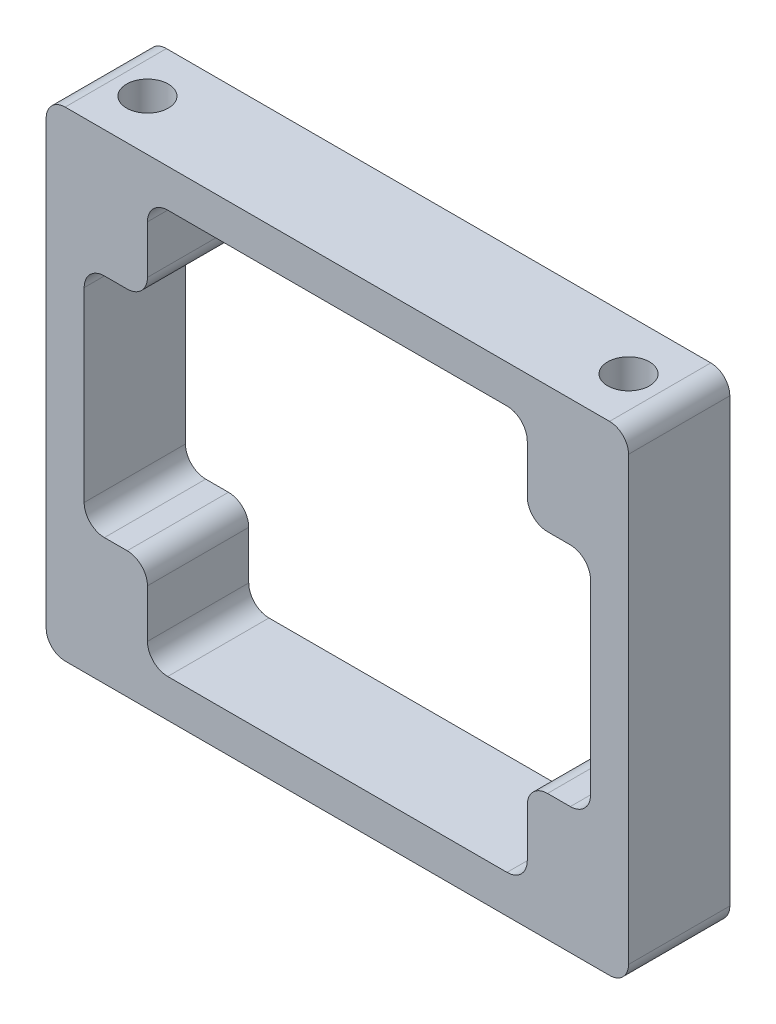
SolidWorks part; units mm, degrees
material "6061 合金"
ref_plane "前视基准面" through (0, 0, 0) normal (0, 0, 1) x (1, 0, 0)
ref_plane "上视基准面" through (0, 0, 0) normal (0, 1, 0) x (1, 0, 0)
ref_plane "右视基准面" through (0, 0, 0) normal (1, 0, 0) x (0, 0, -1)
other "Configuration Table"
sketch "草图1" plane through (0, 0, 0) normal (0, 0, 1) x (1, 0, 0)
  line L1 (-23, -18.95) -> (23, -18.95)
  line L2 (-23, -18.95) -> (-23, 18.95)
  line L3 (-23, 18.95) -> (23, 18.95)
  line L4 (23, -18.95) -> (23, 18.95)
  line L5 (-23, -18.95) -> (23, 18.95) construction
  line L6 (-23, 18.95) -> (23, -18.95) construction
  point P0 (0, 0)
  dimension "D1" = 46
  dimension "D2" = 37.9
extrude "凸台-拉伸1" add sketch "草图1" along normal mid plane 8
sketch "草图2" plane through (0, 18.95, 0) normal (0, 1, 0) x (1, 0, 0)
  line L0 (-19, 0) -> (19, 0) construction
  line L1 (23, -4) -> (23, 4) construction
  point P4 (0, 0)
  dimension "D1" = 4
hole_wizard "M4 螺纹孔1" positions "草图3" profile "草图4" tap size "M4" standard "GB"
sketch "草图3" plane through (0, 18.95, 0) normal (0, 1, 0) x (1, 0, 0)
  point P0 (-19, 0)
  point P3 (19, 0)
sketch "草图4" plane through (-19, 18.95, 0) normal (1, 0, 0) x (0, 0, 1)
  line L0 (0, 0) -> (0, 9.5914)
  line L1 (0, 9.5914) -> (1.65, 8.6)
  line L2 (1.65, 8.6) -> (1.65, 0)
  line L5 (1.65, 0) -> (0, 0)
  line L10 (0, 9.5914) -> (-1.65, 8.6) construction
  line L11 (0, -6.35) -> (0, 107.95) construction
  dimension "螺纹孔钻头直径" = 3.3
  dimension "螺纹孔钻头深度" = 8.6
  dimension "导头角度" = 118
cosmetic thread "孔螺蚊线1" parameters "D1"=6.5, "D2"=4
cosmetic thread "孔螺蚊线2" parameters "D1"=6.5, "D2"=4
mirror "镜向1" about plane through (0, 0, 0) normal (0, 1, 0) of "M4 螺纹孔1"
sketch "草图5" plane through (0, 0, 4) normal (0, 0, 1) x (1, 0, 0)
  line L0 (23, 18.95) -> (-23, 18.95) construction
  line L1 (-15, -15.95) -> (15, -15.95)
  line L2 (-15, -15.95) -> (-15, 15.95)
  line L3 (-15, 15.95) -> (15, 15.95)
  line L4 (15, -15.95) -> (15, 15.95)
  line L5 (-15, -15.95) -> (15, 15.95) construction
  line L6 (-15, 15.95) -> (15, -15.95) construction
  line L7 (23, -18.95) -> (23, 18.95) construction
  point P0 (0, 0)
  dimension "D1" = 3
  dimension "D2" = 8
extrude "切除-拉伸1" cut sketch "草图5" against normal mid plane 38
sketch "草图6" plane through (0, 0, 4) normal (0, 0, 1) x (1, 0, 0)
  line L0 (23, -18.95) -> (23, 18.95) construction
  line L1 (-20, -8.95) -> (20, -8.95)
  line L2 (-20, -8.95) -> (-20, 8.95)
  line L3 (-20, 8.95) -> (20, 8.95)
  line L4 (20, -8.95) -> (20, 8.95)
  line L5 (-20, -8.95) -> (20, 8.95) construction
  line L6 (-20, 8.95) -> (20, -8.95) construction
  line L7 (23, 18.95) -> (-23, 18.95) construction
  point P0 (0, 0)
  dimension "D1" = 3
  dimension "D2" = 10
extrude "切除-拉伸2" cut sketch "草图6" against normal mid plane 68
fillet "圆角1" radius 1.6 12 edges at (-15, -15.95, 0) (15, -15.95, 0) (15, -8.95, 0) (20, -8.95, 0) (20, 8.95, 0) (15, 8.95, 0) (15, 15.95, 0) (-15, 15.95, 0) (-20, -8.95, 0) (-15, -8.95, 0) (-15, 8.95, 0) (-20, 8.95, 0)
fillet "圆角2" radius 1.5 4 edges at (23, -18.95, 0) (-23, -18.95, 0) (23, 18.95, 0) (-23, 18.95, 0)
